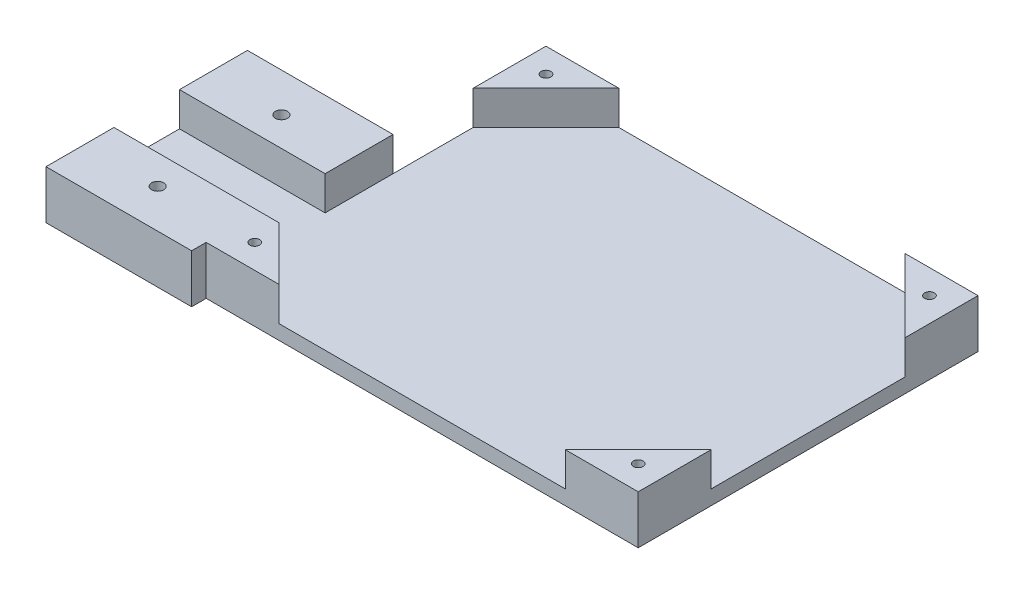
SolidWorks part; units mm, degrees
material "Custom PLA"
ref_plane "Front Plane" through (0, 0, 0) normal (0, 0, 1) x (1, 0, 0)
ref_plane "Top Plane" through (0, 0, 0) normal (0, 1, 0) x (1, 0, 0)
ref_plane "Right Plane" through (0, 0, 0) normal (1, 0, 0) x (0, 0, -1)
sketch "Sketch1" plane through (0, 0, 0) normal (0, 1, 0) x (1, 0, 0)
  line L1 (-44.5, -35) -> (44.5, -35)
  line L2 (-44.5, -35) -> (-44.5, 35)
  line L3 (-44.5, 35) -> (44.5, 35)
  line L4 (44.5, -35) -> (44.5, 35)
  line L5 (0, 35) -> (0, -35) construction
  line L6 (-44.5, 0) -> (44.5, 0) construction
  circle A0 centre (-39.5, 30) radius 1
  circle A1 centre (39.5, 30) radius 1
  circle A2 centre (39.5, -30) radius 1
  circle A3 centre (-39.5, -30) radius 1
  point P0 (0, 0)
  dimension "D3" = 2
  dimension "D1" = 89
  dimension "D2" = 70
  dimension "D4" = 5
  dimension "D5" = 5
extrude "Boss-Extrude1" add sketch "Sketch1" along normal blind 10
sketch "Sketch3" plane through (0, 10, 0) normal (0, 1, 0) x (1, 0, 0)
  line L0 (-44.5, -20) -> (-29.5, -35)
  line L1 (-44.5, 35) -> (-44.5, -35) construction
  line L2 (-44.5, -35) -> (44.5, -35) construction
  line L3 (-29.5, -35) -> (29.5, -35)
  line L4 (29.5, -35) -> (44.5, -20)
  line L5 (44.5, -35) -> (44.5, 35) construction
  line L6 (44.5, -20) -> (44.5, 20)
  line L7 (44.5, 20) -> (29.5, 35)
  line L8 (44.5, 35) -> (-44.5, 35) construction
  line L9 (29.5, 35) -> (-29.5, 35)
  line L10 (-29.5, 35) -> (-44.5, 20)
  line L11 (-44.5, 20) -> (-44.5, -20)
  line L12 (44.5, 20) -> (44.5, 27.0203) construction
  line L13 (-44.5, 20) -> (-44.5, 25.3065) construction
  dimension "D1" = 45
  dimension "D2" = 15
  dimension "D3" = 45
extrude "Cut-Extrude2" cut sketch "Sketch3" against normal blind 7
sketch "Sketch6" plane through (0, 0, 0) normal (0, -1, 0) x (1, 0, 0)
  line L0 (-44.5, -20) -> (-44.5, 20) construction
  line L1 (-44.5, -3.5) -> (-74.5, -3.5)
  line L2 (-44.5, -3.5) -> (-44.5, 38)
  line L3 (-44.5, 38) -> (-74.5, 38)
  line L4 (-74.5, -3.5) -> (-74.5, 38)
  circle A0 centre (-59.5, 30) radius 1.25
  circle A1 centre (-59.5, 4.5) radius 1.25
  point P12 (-39.5, 30)
  dimension "D2" = 2.5
  dimension "D1" = 25.5
  dimension "D3" = 15
  dimension "D4" = 30
  dimension "D5" = 8
  dimension "D6" = 8
extrude "Boss-Extrude2" add sketch "Sketch6" against normal blind 10
sketch "Sketch7" plane through (0, 10, 0) normal (0, 1, 0) x (1, 0, 0)
  line L0 (-74.5, -38) -> (-74.5, 3.5) construction
  line L1 (-74.5, -10.5) -> (-40.5, -10.5)
  line L2 (-74.5, -10.5) -> (-74.5, -24)
  line L3 (-74.5, -24) -> (-40.5, -24)
  line L4 (-40.5, -10.5) -> (-40.5, -24)
  line L5 (-44.5, -20) -> (-29.5, -35) construction
  circle A0 centre (-59.5, -4.5) radius 1.25 construction
  circle A1 centre (-59.5, -30) radius 1.25 construction
  dimension "D1" = 6
  dimension "D2" = 6
extrude "Cut-Extrude3" cut sketch "Sketch7" against normal blind 7
